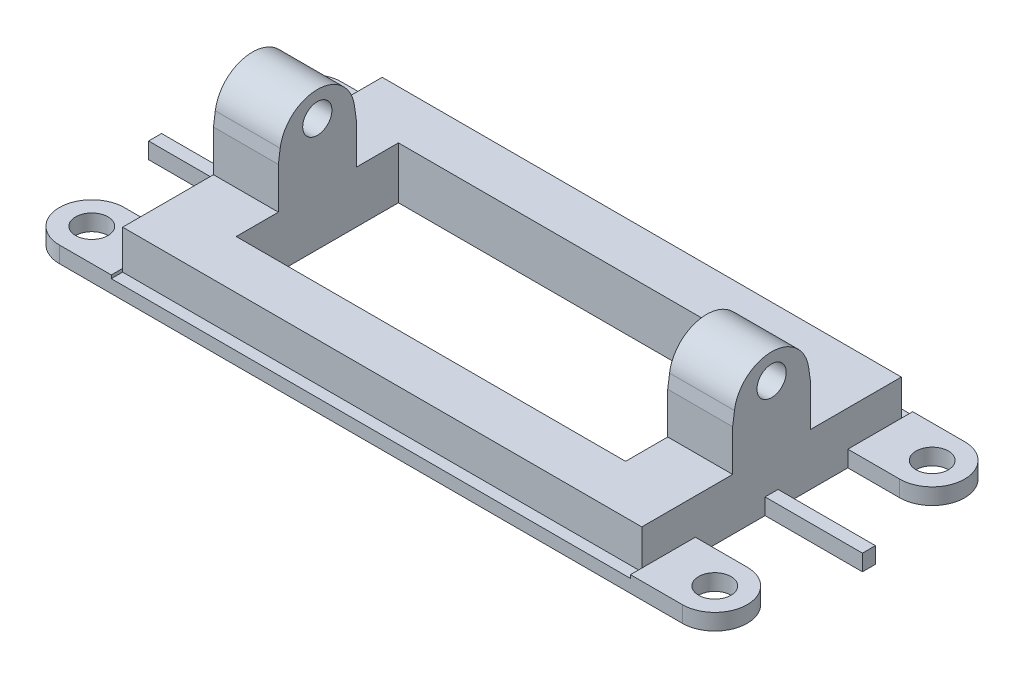
SolidWorks part; units mm, degrees
ref_plane "Front Plane" through (0, 0, 0) normal (0, 0, 1) x (1, 0, 0)
ref_plane "Top Plane" through (0, 0, 0) normal (0, 1, 0) x (1, 0, 0)
ref_plane "Right Plane" through (0, 0, 0) normal (1, 0, 0) x (0, 0, -1)
sketch "Sketch1" plane through (0, 0, 0) normal (1, 0, 0) x (0, 0, -1)
  line L0 (0, 8.8594) -> (0, -2.6719) construction
  line L9 (-20, -2.6719) -> (-21.75, -2.6719)
  line L10 (-21.75, -2.6719) -> (-21.75, -4.6719)
  line L12 (-21.75, -4.6719) -> (21.75, -4.6719)
  line L17 (0, -4.6719) -> (0, -10.1406) construction
  line L39 (-20, -2.6719) -> (-20, 3.3281)
  line L46 (-20, 3.3281) -> (-10.6527, 3.3281)
  line L49 (21.75, -2.6719) -> (21.75, -4.6719)
  line L50 (20, -2.6719) -> (21.75, -2.6719)
  line L51 (20, -2.6719) -> (20, 3.3281)
  line L52 (20, 3.3281) -> (10.6527, 3.3281)
  line L58 (-6, 3.3281) -> (-6, 9.7012)
  line L59 (-10.6527, 3.3281) -> (-6, 3.3281)
  line L60 (6, 3.3281) -> (6, 9.7012)
  line L62 (6, 3.3281) -> (10.6527, 3.3281)
  line L63 (-6, 9.7012) -> (-5.7212, 11.7169)
  line L64 (5.7212, 11.7169) -> (6, 9.7012)
  circle A7 centre (0, 12.8281) radius 2.25
  arc A8 (-5.7212, 11.7169) -> (5.7212, 11.7169) centre (0, 10.9254) cw
  dimension "D2" = 17.5
  dimension "D6" = 4.5
  dimension "D3" = 20
  dimension "D4" = 2
  dimension "D5" = 6
  dimension "D7" = 6
  dimension "D10" = 17.5
extrude "Boss-Extrude1" add sketch "Sketch1" along normal mid plane 80
sketch "Sketch3" plane through (0, -4.6719, 0) normal (0, 1, 0) x (1, 0, 0)
  line L0 (0, 29.6975) -> (0, -28.0784) construction
  line L1 (-40, 5.7212) -> (-40, -5.7212) construction
  line L3 (-40, 21.75) -> (-48, 21.75)
  line L4 (-48, 11.75) -> (-40, 11.75)
  line L7 (-40, 21.75) -> (-40, 11.75)
  line L9 (-40, -21.75) -> (-40, 21.75) construction
  line L10 (40, 21.75) -> (48, 21.75)
  line L11 (48, 11.75) -> (40, 11.75)
  line L12 (40, 21.75) -> (40, 11.75)
  line L13 (-13.6299, 0) -> (8.9506, 0) construction
  line L14 (40, -21.75) -> (40, -11.75)
  line L15 (48, -11.75) -> (40, -11.75)
  line L16 (40, -21.75) -> (48, -21.75)
  line L17 (-40, -21.75) -> (-48, -21.75)
  line L18 (-48, -11.75) -> (-40, -11.75)
  line L19 (-40, -21.75) -> (-40, -11.75)
  line L21 (-40, -1) -> (-55, -1)
  line L22 (-40, -1) -> (-40, 1)
  line L23 (-40, 1) -> (-55, 1)
  line L24 (-55, -1) -> (-55, 1)
  line L25 (40, 1) -> (55, 1)
  line L26 (55, -1) -> (55, 1)
  line L27 (40, -1) -> (55, -1)
  line L28 (40, -1) -> (40, 1)
  arc A0 (-48, 21.75) -> (-48, 11.75) centre (-48, 16.75) ccw
  circle A1 centre (-48, 16.75) radius 2.5
  circle A4 centre (48, 16.75) radius 2.5
  arc A5 (48, 21.75) -> (48, 11.75) centre (48, 16.75) cw
  arc A6 (48, -21.75) -> (48, -11.75) centre (48, -16.75) ccw
  arc A7 (-48, -21.75) -> (-48, -11.75) centre (-48, -16.75) cw
  circle A8 centre (48, -16.75) radius 2.5
  circle A9 centre (-48, -16.75) radius 2.5
  point P8 (0, 0)
  point P38 (-40, 0)
  dimension "D2" = 5
  dimension "D3" = 5
  dimension "D1" = 8
  dimension "D4" = 2
  dimension "D5" = 15
extrude "Boss-Extrude2" add sketch "Sketch3" along normal blind 2.5
sketch "Sketch2" plane through (0, -2.6719, 0) normal (0, 1, 0) x (1, 0, 0)
  line L11 (30, -12.5) -> (-30, -12.5)
  line L12 (30, -12.5) -> (30, 12.5)
  line L13 (30, 12.5) -> (-30, 12.5)
  line L14 (-30, -12.5) -> (-30, 12.5)
  line L15 (30, -12.5) -> (-30, 12.5) construction
  line L16 (30, 12.5) -> (-30, -12.5) construction
  point P0 (0, 0)
  point P1 (0, 0)
  point P2 (0, 0)
  dimension "D1" = 60
  dimension "D2" = 25
extrude "Cut-Extrude2" cut sketch "Sketch2" against normal blind 60 and the other way blind 60
